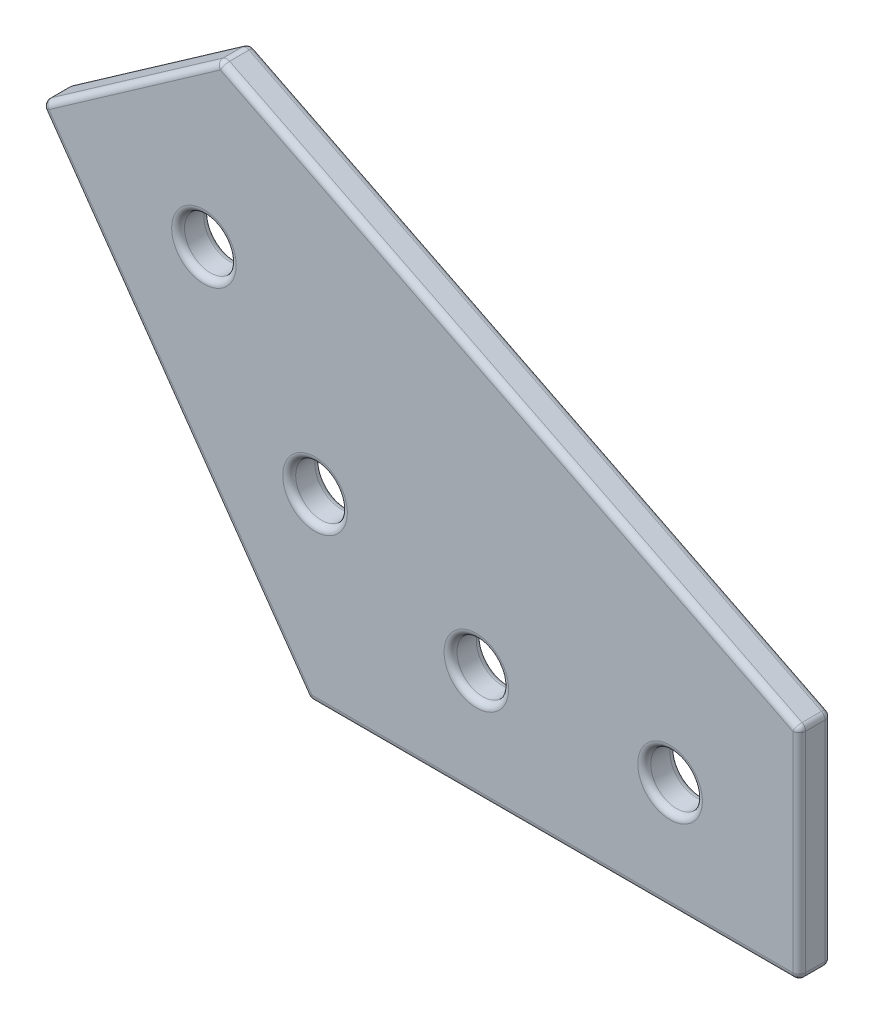
SolidWorks part; units mm, degrees
ref_plane "Front Plane" through (0, 0, 0) normal (0, 0, 1) x (1, 0, 0)
ref_plane "Top Plane" through (0, 0, 0) normal (0, 1, 0) x (1, 0, 0)
ref_plane "Right Plane" through (0, 0, 0) normal (1, 0, 0) x (0, 0, -1)
sketch "Sketch1" plane through (0, 0, 0) normal (0, 0, 1) x (1, 0, 0)
  line L0 (-66.4603, 24.3885) -> (-38.6092, 43.8901)
  line L1 (-38.6092, 43.8901) -> (51.124, -1)
  line L2 (51.124, -1) -> (51.124, -35)
  line L3 (51.124, -35) -> (-24.876, -35)
  line L4 (-24.876, -35) -> (-66.4603, 24.3885)
  point P6 (0, 0)
  dimension "D1" = 76
  dimension "D2" = 125
  dimension "D3" = 34
  dimension "D4" = 34
  dimension "D5" = 72.5
  dimension "D6" = 35
  dimension "D7" = 90
  dimension "D8" = 51.124
extrude "Boss-Extrude1" add sketch "Sketch1" along normal blind 5
sketch "Sketch2" plane through (0, 0, 5) normal (0, 0, 1) x (1, 0, 0)
  line L0 (-38.6092, 43.8901) -> (16.6303, -35) construction
  line L3 (-24.876, -35) -> (51.124, -35) construction
  line L4 (-66.4603, 24.3885) -> (-24.876, -35) construction
  line L5 (51.124, -1) -> (-48.6831, -1) construction
  line L6 (-52.5347, 34.1393) -> (-4.1229, -35) construction
  line L7 (-38.6092, 43.8901) -> (-66.4603, 24.3885) construction
  line L8 (51.124, -18) -> (-36.7796, -18) construction
  line L9 (51.124, -35) -> (51.124, -1) construction
  line L10 (21.124, -18) -> (-66.7796, -18) construction
  circle A0 centre (31.124, -18) radius 4
  circle A1 centre (1.124, -18) radius 4
  circle A2 centre (-41.0632, 17.7563) radius 4
  circle A3 centre (-23.8559, -6.8183) radius 4
  point P2 (0, 0)
  point P21 (0, 0)
  point P28 (0, 0)
  dimension "D1" = 8
  dimension "D4" = 8
  dimension "D3" = 20
  dimension "D6" = 20
  dimension "D7" = 30
  dimension "D8" = 30
  dimension "D9" = 17
  dimension "D2" = 2
  dimension "D5" = 2
extrude "Cut-Extrude1" cut sketch "Sketch2" against normal through all contours A0 | A1 | A3 | A2
fillet "Fillet1" radius 1 23 edges at (-52.5347, 34.1393, 5) (6.2574, 21.4451, 5) (51.124, -18, 5) (13.124, -35, 5) (-45.6682, -5.3057, 5) (35.124, -18, 5) (5.124, -18, 5) (-19.8559, -6.8183, 5) (-37.0632, 17.7563, 5) (13.124, -35, 0) (51.124, -18, 0) (6.2574, 21.4451, 0) (-52.5347, 34.1393, 0) (-45.6682, -5.3057, 0) (-37.0632, 17.7563, 0) (-19.8559, -6.8183, 0) (5.124, -18, 0) (35.124, -18, 0) (-38.6092, 43.8901, 2.5) (51.124, -1, 2.5) (51.124, -35, 2.5) (-24.876, -35, 2.5) (-66.4603, 24.3885, 2.5)
